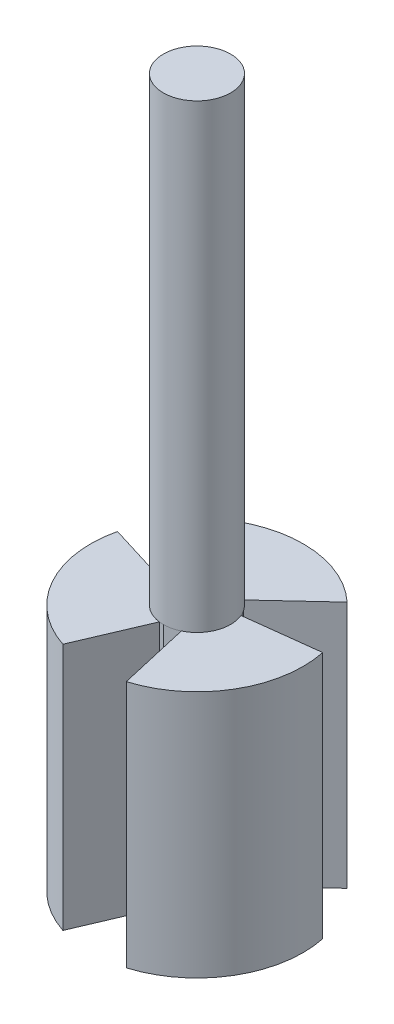
SolidWorks part; units mm, degrees
material "AISI 347 Annealed Stainless Steel (SS)"
ref_plane "Front Plane" through (0, 0, 0) normal (0, 0, 1) x (1, 0, 0)
ref_plane "Top Plane" through (0, 0, 0) normal (0, 1, 0) x (1, 0, 0)
ref_plane "Right Plane" through (0, 0, 0) normal (1, 0, 0) x (0, 0, -1)
sketch "Sketch1" plane through (0, 0, 0) normal (0, 1, 0) x (1, 0, 0)
  circle A0 centre (0, 0) radius 9.5
  dimension "D1" = 19
extrude "Boss-Extrude1" add sketch "Sketch1" along normal blind 200
sketch "Sketch2" plane through (0, 0, 0) normal (0, -1, 0) x (1, 0, 0)
  circle A0 centre (0, 0) radius 30
  circle A2 centre (0, 0) radius 9.5
  circle A3 centre (0, 0) radius 9.5
  dimension "D1" = 60
  dimension "D2" = 0
extrude "Boss-Extrude2" add sketch "Sketch2" against normal blind 70
sketch "Sketch4" plane through (0, 70, 0) normal (0, 1, 0) x (1, 0, 0)
  line L0 (-10.9396, -32.2027) -> (-1.213, -9.4222)
  line L1 (-1.213, -9.4222) -> (0, -9.5)
  line L2 (0, -9.5) -> (4.1338, -8.5535)
  line L3 (4.1338, -8.5535) -> (9.5489, -32.2027)
  line L4 (-10.9396, -32.2027) -> (9.5489, -32.2027)
  circle A2 centre (0, 0) radius 9.5 construction
  circle A3 centre (0, 0) radius 9.5 construction
extrude "Cut-Extrude1" cut sketch "Sketch4" against normal through all
pattern_circular "CirPattern1" count 3 over 360 about axis through (0, 0, 0) along (0, 1, 0) of "Cut-Extrude1"
